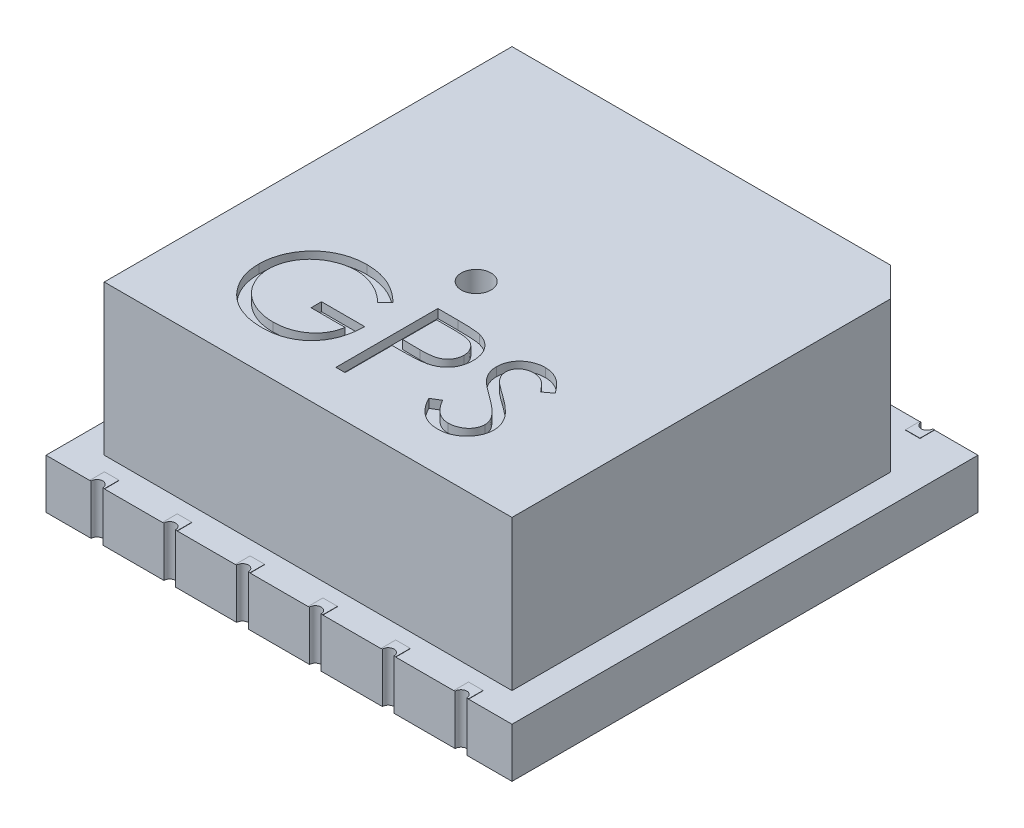
SolidWorks part; units mm, degrees
ref_plane "Front Plane" through (0, 0, 0) normal (0, 0, 1) x (1, 0, 0)
ref_plane "Top Plane" through (0, 0, 0) normal (0, 1, 0) x (1, 0, 0)
ref_plane "Right Plane" through (0, 0, 0) normal (1, 0, 0) x (0, 0, -1)
sketch "Sketch1" plane through (0, 0, 0) normal (0, 1, 0) x (1, 0, 0)
  line L1 (0, 0) -> (16, 0)
  line L2 (0, 0) -> (0, 16)
  line L3 (0, 16) -> (16, 16)
  line L4 (16, 0) -> (16, 16)
  dimension "D1" = 16
  dimension "D2" = 16
extrude "Boss-Extrude1" add sketch "Sketch1" along normal blind 1.7
sketch "Sketch2" plane through (0, 1.7, 0) normal (0, 1, 0) x (1, 0, 0)
  line L0 (0, 0) -> (16, 0) construction
  line L1 (15, 1) -> (1, 1)
  line L2 (15, 1) -> (15, 14)
  line L3 (14, 15) -> (1, 15)
  line L4 (1, 1) -> (1, 15)
  line L5 (16, 16) -> (0, 16) construction
  line L6 (0, 16) -> (0, 0) construction
  line L7 (16, 0) -> (16, 16) construction
  line L8 (14, 15) -> (15, 14)
  dimension "D1" = 1
  dimension "D2" = 1
  dimension "D3" = 1
  dimension "D4" = 1
extrude "Boss-Extrude2" add sketch "Sketch2" along normal blind 5.15
sketch "Sketch4" plane through (0, 1.7, 0) normal (0, 1, 0) x (1, 0, 0)
  line L0 (12.0075, 16) -> (11.5075, 16)
  line L1 (14.5075, 16) -> (14.0075, 16)
  line L2 (14.5075, 16) -> (14.5075, 15.5)
  line L3 (14.5075, 15.5) -> (14.0075, 15.5)
  line L4 (14.0075, 16) -> (14.0075, 15.5)
  line L5 (12.0075, 16) -> (12.0075, 15.5)
  line L6 (12.0075, 15.5) -> (11.5075, 15.5)
  line L7 (11.5075, 16) -> (11.5075, 15.5)
  line L8 (9.5075, 16) -> (9.0075, 16)
  line L9 (16, 16) -> (0, 16) construction
  line L10 (9.5075, 16) -> (9.5075, 15.5)
  line L11 (9.5075, 15.5) -> (9.0075, 15.5)
  line L12 (9.0075, 16) -> (9.0075, 15.5)
  line L13 (7.0075, 16) -> (6.5075, 16)
  line L14 (7.0075, 16) -> (7.0075, 15.5)
  line L15 (7.0075, 15.5) -> (6.5075, 15.5)
  line L16 (6.5075, 16) -> (6.5075, 15.5)
  line L17 (4.5075, 16) -> (4.0075, 16)
  line L18 (4.5075, 16) -> (4.5075, 15.5)
  line L19 (4.5075, 15.5) -> (4.0075, 15.5)
  line L20 (4.0075, 16) -> (4.0075, 15.5)
  line L21 (2.0075, 16) -> (1.5075, 16)
  line L22 (2.0075, 16) -> (2.0075, 15.5)
  line L23 (2.0075, 15.5) -> (1.5075, 15.5)
  line L24 (1.5075, 16) -> (1.5075, 15.5)
  line L25 (16, 8) -> (-0.3595, 8) construction
  line L26 (16, 0) -> (16, 16) construction
  line L27 (1.5075, 0) -> (1.5075, 0.5)
  line L28 (2.0075, 0.5) -> (1.5075, 0.5)
  line L29 (2.0075, 0) -> (2.0075, 0.5)
  line L30 (2.0075, 0) -> (1.5075, 0)
  line L31 (4.0075, 0) -> (4.0075, 0.5)
  line L32 (4.5075, 0.5) -> (4.0075, 0.5)
  line L33 (4.5075, 0) -> (4.5075, 0.5)
  line L34 (4.5075, 0) -> (4.0075, 0)
  line L35 (6.5075, 0) -> (6.5075, 0.5)
  line L36 (7.0075, 0.5) -> (6.5075, 0.5)
  line L37 (7.0075, 0) -> (7.0075, 0.5)
  line L38 (7.0075, 0) -> (6.5075, 0)
  line L39 (9.0075, 0) -> (9.0075, 0.5)
  line L40 (9.5075, 0.5) -> (9.0075, 0.5)
  line L41 (9.5075, 0) -> (9.5075, 0.5)
  line L42 (9.5075, 0) -> (9.0075, 0)
  line L43 (11.5075, 0) -> (11.5075, 0.5)
  line L44 (12.0075, 0.5) -> (11.5075, 0.5)
  line L45 (12.0075, 0) -> (12.0075, 0.5)
  line L46 (14.0075, 0) -> (14.0075, 0.5)
  line L47 (14.5075, 0.5) -> (14.0075, 0.5)
  line L48 (14.5075, 0) -> (14.5075, 0.5)
  line L49 (14.5075, 0) -> (14.0075, 0)
  line L50 (12.0075, 0) -> (11.5075, 0)
  dimension "D1" = 0.5
  dimension "D2" = 0.5
  dimension "D3" = 6
extrude "Boss-Extrude3" add sketch "Sketch4" along normal blind 0.01
sketch "Sketch3" plane through (0, 1.71, 0) normal (0, 1, 0) x (1, 0, 0)
  line L0 (16, 16) -> (14.5075, 16) construction
  line L1 (16, 8) -> (0, 8) construction
  line L2 (16, 0) -> (16, 16) construction
  line L3 (0, 16) -> (0, 0) construction
  line L4 (14.4491, 16) -> (14.0491, 16)
  line L5 (11.9491, 16) -> (11.5491, 16)
  line L6 (9.4491, 16) -> (9.0491, 16)
  line L7 (6.9491, 16) -> (6.5491, 16)
  line L8 (4.4491, 16) -> (4.0491, 16)
  line L9 (1.9491, 16) -> (1.5491, 16)
  line L10 (1.9491, 0) -> (1.5491, 0)
  line L11 (4.4491, 0) -> (4.0491, 0)
  line L12 (6.9491, 0) -> (6.5491, 0)
  line L13 (9.4491, 0) -> (9.0491, 0)
  line L14 (11.9491, 0) -> (11.5491, 0)
  line L15 (14.4491, 0) -> (14.0491, 0)
  arc A0 (14.0491, 16) -> (14.4491, 16) centre (14.2491, 16) ccw
  arc A1 (11.5491, 16) -> (11.9491, 16) centre (11.7491, 16) ccw
  arc A2 (9.0491, 16) -> (9.4491, 16) centre (9.2491, 16) ccw
  arc A3 (6.5491, 16) -> (6.9491, 16) centre (6.7491, 16) ccw
  arc A4 (4.0491, 16) -> (4.4491, 16) centre (4.2491, 16) ccw
  arc A5 (1.5491, 16) -> (1.9491, 16) centre (1.7491, 16) ccw
  arc A6 (1.5491, 0) -> (1.9491, 0) centre (1.7491, 0) cw
  arc A7 (4.0491, 0) -> (4.4491, 0) centre (4.2491, 0) cw
  arc A8 (6.5491, 0) -> (6.9491, 0) centre (6.7491, 0) cw
  arc A9 (9.0491, 0) -> (9.4491, 0) centre (9.2491, 0) cw
  arc A10 (11.5491, 0) -> (11.9491, 0) centre (11.7491, 0) cw
  arc A11 (14.0491, 0) -> (14.4491, 0) centre (14.2491, 0) cw
  dimension "D1" = 0.2
  dimension "D2" = 6
extrude "Cut-Extrude1" cut sketch "Sketch3" against normal through all
sketch "Sketch5" plane through (0, 6.85, 0) normal (0, 1, 0) x (1, 0, 0)
  line L0 (7.0075, 0) -> (9.0075, 0) construction
  line L1 (0, 16) -> (0, 0) construction
  circle A0 centre (7.37, 7.4) radius 0.51
  dimension "D3" = 1.02
  dimension "D1" = 7.4
  dimension "D2" = 7.37
extrude "Cut-Extrude2" cut sketch "Sketch5" against normal through all
sketch "Sketch6" plane through (0, 6.85, 0) normal (0, 1, 0) x (1, 0, 0)
  line L0 (1, 15) -> (1, 1) construction
  line L1 (1, 1) -> (15, 1) construction
  text T0 "GPS"
  point P1 (2.8479, 2.4392)
  dimension "D1" = 1.8479
  dimension "D2" = 1.4392
extrude "Cut-Extrude3" cut sketch "Sketch6" against normal blind 0.3
